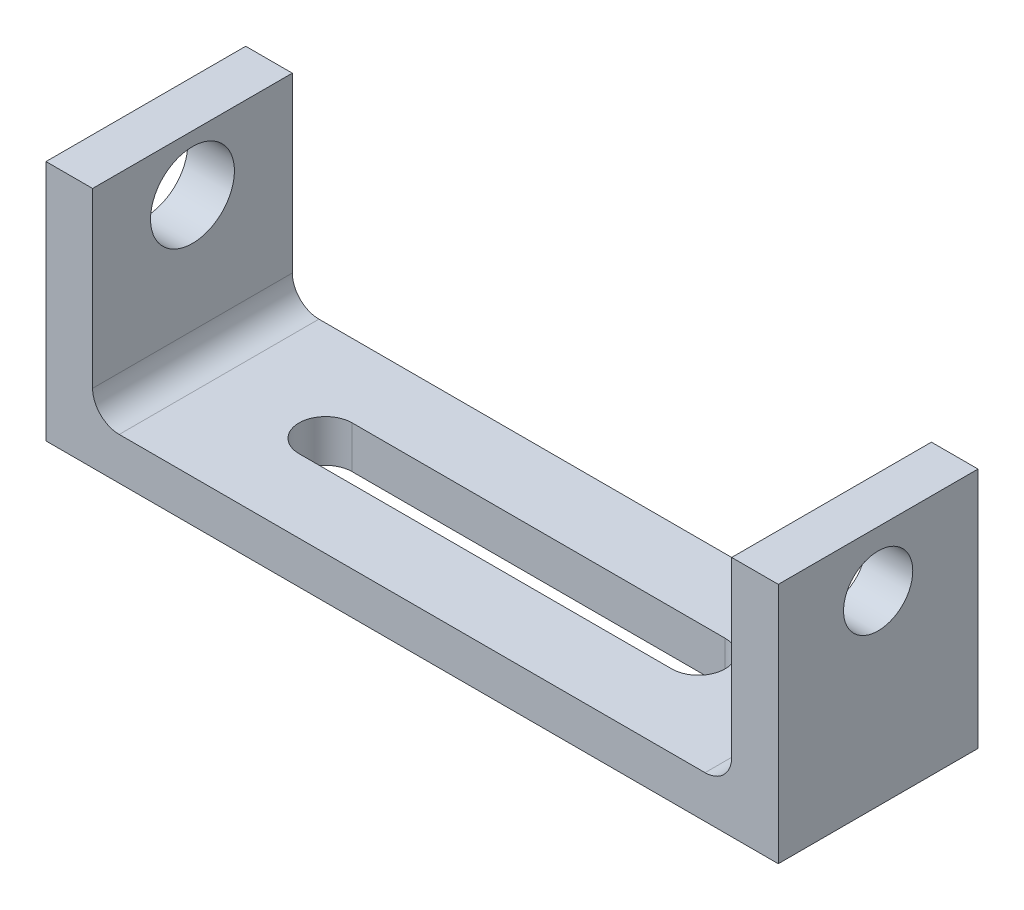
SolidWorks part; units mm, degrees
ref_plane "Front Plane" through (0, 0, 0) normal (0, 0, 1) x (1, 0, 0)
ref_plane "Top Plane" through (0, 0, 0) normal (0, 1, 0) x (1, 0, 0)
ref_plane "Right Plane" through (0, 0, 0) normal (1, 0, 0) x (0, 0, -1)
sketch "Sketch1" plane through (0, 0, 0) normal (0, 1, 0) x (1, 0, 0)
  line L1 (-27.5, -7.5) -> (27.5, -7.5)
  line L2 (-27.5, -7.5) -> (-27.5, 7.5)
  line L3 (-27.5, 7.5) -> (27.5, 7.5)
  line L4 (27.5, -7.5) -> (27.5, 7.5)
  line L5 (-27.5, -7.5) -> (27.5, 7.5) construction
  line L6 (-27.5, 7.5) -> (27.5, -7.5) construction
  point P0 (0, 0)
  dimension "D1" = 55
  dimension "D2" = 15
extrude "Boss-Extrude1" add sketch "Sketch1" along normal blind 3.175
sketch "Sketch2" plane through (0, 3.175, 0) normal (0, 1, 0) x (1, 0, 0)
  line L0 (-27.5, 0) -> (27.5, 0) construction
  line L1 (-27.5, 7.5) -> (-24, 7.5)
  line L2 (-27.5, 7.5) -> (-27.5, -7.5)
  line L3 (-27.5, -7.5) -> (-24, -7.5)
  line L4 (-24, 7.5) -> (-24, -7.5)
  line L5 (-27.5, 7.5) -> (-27.5, -7.5) construction
  line L6 (27.5, -7.5) -> (27.5, 7.5) construction
  line L7 (0, 7.5) -> (0, -7.5) construction
  line L8 (27.5, 7.5) -> (-27.5, 7.5) construction
  line L9 (-27.5, -7.5) -> (27.5, -7.5) construction
  line L10 (27.5, -7.5) -> (24, -7.5)
  line L11 (24, 7.5) -> (24, -7.5)
  line L12 (27.5, 7.5) -> (24, 7.5)
  line L13 (27.5, 7.5) -> (27.5, -7.5)
  dimension "D1" = 3.5
  dimension "D2" = 15
  dimension "D3" = 27.5
extrude "Boss-Extrude2" add sketch "Sketch2" along normal blind 15
fillet "Fillet1" radius 2 2 edges at (-24, 3.175, 0) (24, 3.175, 0)
sketch "Sketch3" plane through (0, 3.175, 0) normal (0, 1, 0) x (1, 0, 0)
  line L0 (-14, 0) -> (14, 0) construction
  line L1 (-14, 2) -> (14, 2)
  line L2 (-14, -2) -> (14, -2)
  line L3 (0, -7.5) -> (0, 7.5) construction
  line L4 (-22, -7.5) -> (22, -7.5) construction
  line L5 (22, 7.5) -> (-22, 7.5) construction
  arc A0 (-14, 2) -> (-14, -2) centre (-14, 0) ccw
  arc A1 (14, -2) -> (14, 2) centre (14, 0) ccw
  point P3 (0, 0)
  point P8 (16, 0)
  dimension "D2" = 30
  dimension "D1" = 4
extrude "Cut-Extrude1" cut sketch "Sketch3" against normal through all
sketch "Sketch4" plane through (27.5, 0, 0) normal (1, 0, 0) x (0, 0, -1)
  line L1 (-7.5, 0) -> (7.5, 0) construction
  line L2 (7.5, 18.175) -> (7.5, 0) construction
  circle A0 centre (0, 14) radius 2.6
  dimension "D1" = 5.2
  dimension "D3" = 7.5
  dimension "D2" = 14
extrude "Cut-Extrude2" cut sketch "Sketch4" against normal blind 10
sketch "Sketch5" plane through (-27.5, 0, 0) normal (-1, 0, 0) x (0, 0, 1)
  circle A0 centre (0, 14) radius 3.15
  dimension "D1" = 6.3
extrude "Cut-Extrude3" cut sketch "Sketch5" against normal blind 5
